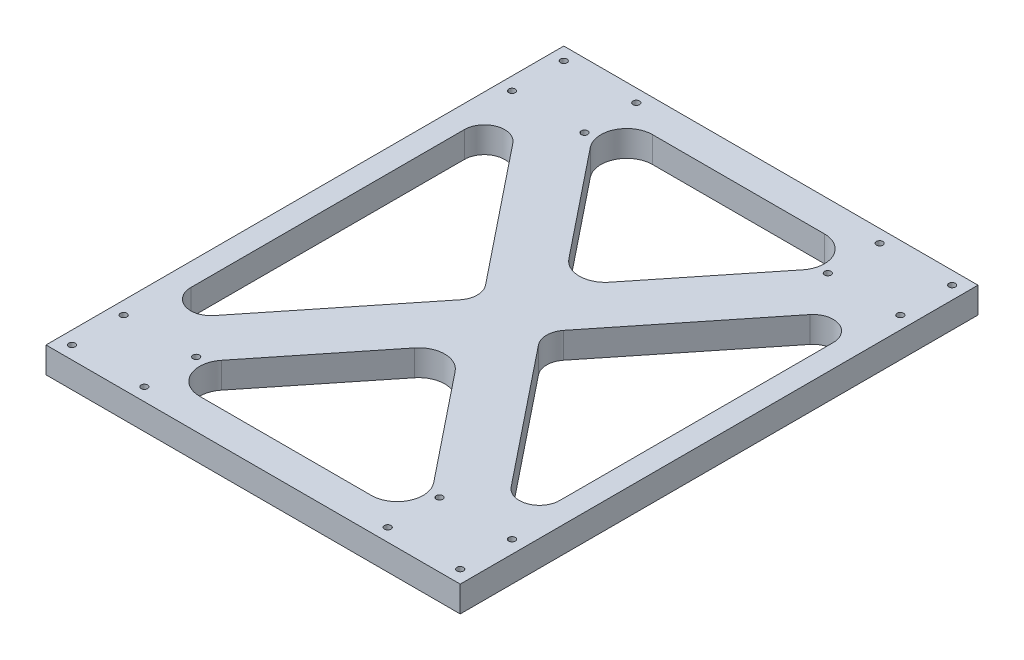
SolidWorks part; units mm, degrees
ref_plane "Front Plane" through (0, 0, 0) normal (0, 0, 1) x (1, 0, 0)
ref_plane "Top Plane" through (0, 0, 0) normal (0, 1, 0) x (1, 0, 0)
ref_plane "Right Plane" through (0, 0, 0) normal (1, 0, 0) x (0, 0, -1)
sketch "Sketch1" plane through (0, 0, 0) normal (0, 1, 0) x (1, 0, 0)
  line L1 (-101.6, -127) -> (101.6, -127)
  line L2 (-101.6, -127) -> (-101.6, 127)
  line L3 (-101.6, 127) -> (101.6, 127)
  line L4 (101.6, -127) -> (101.6, 127)
  line L5 (-101.6, -127) -> (101.6, 127) construction
  line L6 (-101.6, 127) -> (101.6, -127) construction
  line L9 (-101.6, 127) -> (0, 0)
  line L10 (0, 0) -> (-101.6, -127)
  line L11 (0, 0) -> (101.6, 127)
  line L12 (101.6, -127) -> (0, 0)
  line L13 (-72.8462, 73.2691) -> (-19.1815, 6.1882)
  line L14 (-19.1815, -6.1882) -> (-72.8462, -73.2691)
  line L15 (-90.4875, -67.0809) -> (-90.4875, 67.0809)
  line L16 (-110.2774, 120.0581) -> (-8.6774, -6.9419) construction
  line L17 (-90.4875, -127) -> (-90.4875, 127) construction
  line L18 (-8.6774, 6.9419) -> (-110.2774, -120.0581) construction
  line L19 (0, 127) -> (0, -127) construction
  line L20 (72.8462, 73.2691) -> (19.1815, 6.1882)
  line L21 (90.4875, -67.0809) -> (90.4875, 67.0809)
  line L22 (19.1815, -6.1882) -> (72.8462, -73.2691)
  line L23 (-42.1461, 111.125) -> (42.1461, 111.125)
  line L24 (9.917, 37.8087) -> (52.0632, 90.4914)
  line L25 (-52.0632, 90.4914) -> (-9.917, 37.8087)
  line L26 (0, 25.4124) -> (68.5701, 111.125) construction
  line L27 (-68.5701, 111.125) -> (0, 25.4124) construction
  line L28 (-68.5701, 111.125) -> (68.5701, 111.125) construction
  line L29 (-101.6, 0) -> (101.6, 0) construction
  line L30 (-52.0632, -90.4914) -> (-9.917, -37.8087)
  line L31 (9.917, -37.8087) -> (52.0632, -90.4914)
  line L32 (-42.1461, -111.125) -> (42.1461, -111.125)
  arc A0 (-19.1815, 6.1882) -> (-19.1815, -6.1882) centre (-26.9168, 0) cw
  arc A1 (-72.8462, -73.2691) -> (-90.4875, -67.0809) centre (-80.5815, -67.0809) cw
  arc A2 (-90.4875, 67.0809) -> (-72.8462, 73.2691) centre (-80.5815, 67.0809) cw
  arc A3 (90.4875, 67.0809) -> (72.8462, 73.2691) centre (80.5815, 67.0809) ccw
  arc A4 (19.1815, 6.1882) -> (19.1815, -6.1882) centre (26.9168, 0) ccw
  arc A5 (72.8462, -73.2691) -> (90.4875, -67.0809) centre (80.5815, -67.0809) ccw
  arc A6 (9.917, 37.8087) -> (-9.917, 37.8087) centre (0, 45.7423) cw
  arc A7 (42.1461, 111.125) -> (52.0632, 90.4914) centre (42.1461, 98.425) cw
  arc A8 (-42.1461, 111.125) -> (-52.0632, 90.4914) centre (-42.1461, 98.425) ccw
  arc A9 (9.917, -37.8087) -> (-9.917, -37.8087) centre (0, -45.7423) ccw
  arc A10 (42.1461, -111.125) -> (52.0632, -90.4914) centre (42.1461, -98.425) ccw
  arc A11 (-42.1461, -111.125) -> (-52.0632, -90.4914) centre (-42.1461, -98.425) cw
  point P0 (0, 0)
  dimension "D4" = 9.906
  dimension "D6" = 12.7
  dimension "D1" = 203.2
  dimension "D2" = 254
  dimension "D3" = 11.1125
  dimension "D5" = 15.875
extrude "Original Extrustion" add sketch "Sketch1" along normal blind 12.7 contours L9 L11 L3 A8 L23 A7 L24 A6 L25 | L10 L9 L2 L15 A2 L13 A0 L14 A1 | L1 L12 L10 L32 A11 L30 A9 L31 A10 | L12 L4 L11 A5 L22 A4 L20 A3 L21
sketch "Sketch2" plane through (0, 12.7, 0) normal (0, 1, 0) x (1, 0, 0)
  line L0 (-95.25, -120.65) -> (-59.69, -120.65) construction
  line L1 (-95.25, -120.65) -> (-95.25, -95.25) construction
  line L2 (-101.6, 0) -> (101.6, 0) construction
  line L3 (0, 127) -> (0, -127) construction
  line L4 (-101.6, 127) -> (-101.6, -127)
  line L5 (-101.6, -127) -> (101.6, -127)
  line L6 (101.6, -127) -> (101.6, 127)
  line L7 (101.6, 127) -> (-101.6, 127)
  line L8 (-101.6, 127) -> (-101.6, -127)
  line L9 (-101.6, -127) -> (101.6, -127)
  line L10 (101.6, -127) -> (101.6, 127)
  line L11 (101.6, 127) -> (-101.6, 127)
  circle A0 centre (-95.25, -120.65) radius 1.6
  circle A1 centre (-59.69, -120.65) radius 1.6
  circle A2 centre (-59.69, -95.25) radius 1.6
  circle A3 centre (-95.25, -95.25) radius 1.6
  circle A4 centre (-59.69, 120.65) radius 1.6
  circle A5 centre (-59.69, 95.25) radius 1.6
  circle A6 centre (-95.25, 95.25) radius 1.6
  circle A7 centre (-95.25, 120.65) radius 1.6
  circle A8 centre (59.69, 120.65) radius 1.6
  circle A9 centre (95.25, 120.65) radius 1.6
  circle A10 centre (59.69, 95.25) radius 1.6
  circle A11 centre (95.25, 95.25) radius 1.6
  circle A12 centre (59.69, -95.25) radius 1.6
  circle A13 centre (95.25, -95.25) radius 1.6
  circle A14 centre (95.25, -120.65) radius 1.6
  circle A15 centre (59.69, -120.65) radius 1.6
  dimension "D2" = 2
  dimension "D7" = 3.2
  dimension "D4" = 90
  dimension "D5" = 35.56
  dimension "D6" = 25.4
  dimension "D8" = 6.35
  dimension "D9" = 6.35
  dimension "D1" = 0
  dimension "D3" = 2
extrude "Holes for Wheels to mount" cut sketch "Sketch2" against normal through all both and the other way through all contours A7 | A4 | A6 | A5 | A3 | A2 | A0 | A1 | A12 | A13 | A15 | A14 | A8 | A10 | A11 | A9
